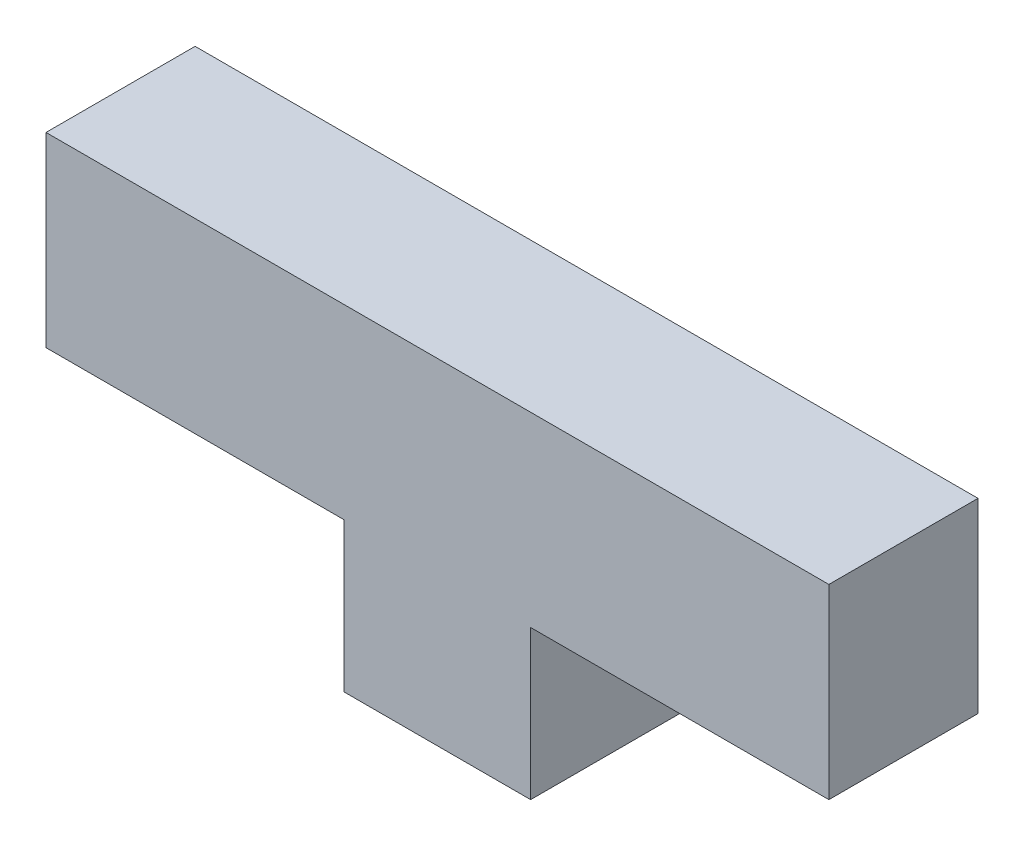
SolidWorks part; units mm, degrees
ref_plane "Front Plane" through (0, 0, 0) normal (0, 0, 1) x (1, 0, 0)
ref_plane "Top Plane" through (0, 0, 0) normal (0, 1, 0) x (1, 0, 0)
ref_plane "Right Plane" through (0, 0, 0) normal (1, 0, 0) x (0, 0, -1)
sketch "Sketch1" plane through (0, 0, 0) normal (0, 0, 1) x (1, 0, 0)
  line L0 (-3.175, -3.175) -> (-3.175, -8.255)
  line L1 (-13.335, 3.175) -> (13.335, 3.175)
  line L2 (-13.335, 3.175) -> (-13.335, -3.175)
  line L3 (-13.335, -3.175) -> (13.335, -3.175) construction
  line L4 (13.335, 3.175) -> (13.335, -3.175)
  line L5 (-13.335, 3.175) -> (13.335, -3.175) construction
  line L6 (-13.335, -3.175) -> (13.335, 3.175) construction
  line L7 (-3.175, -8.255) -> (3.175, -8.255)
  line L8 (3.175, -8.255) -> (3.175, -3.175)
  line L9 (3.175, -3.175) -> (13.335, -3.175)
  line L10 (-3.175, -3.175) -> (-13.335, -3.175)
  line L11 (13.335, -3.175) -> (13.335, -8.255) construction
  point P0 (0, 0)
  point P9 (0, 0)
  dimension "D1" = 6.35
  dimension "D2" = 5.08
  dimension "D3" = 6.35
extrude "Boss-Extrude1" add sketch "Sketch1" along normal blind 5.08
